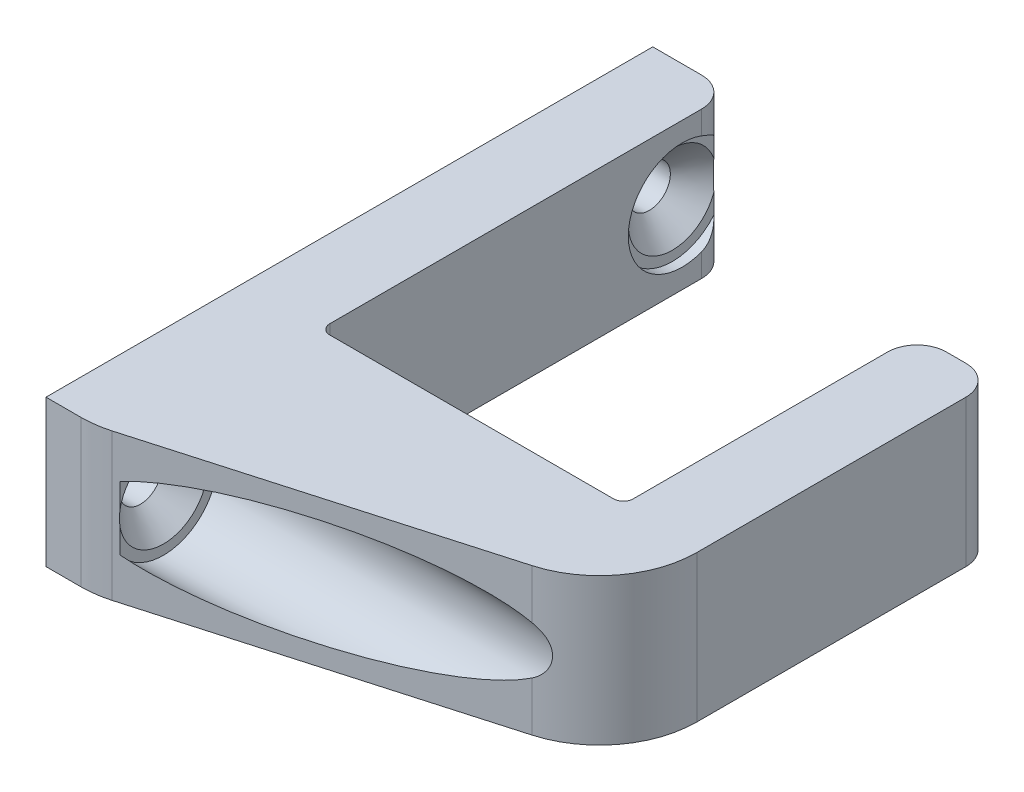
SolidWorks part; units mm, degrees
material "ABS"
ref_plane "Plan de face" through (0, 0, 0) normal (0, 0, 1) x (1, 0, 0)
ref_plane "Plan de dessus" through (0, 0, 0) normal (0, 1, 0) x (1, 0, 0)
ref_plane "Plan de droite" through (0, 0, 0) normal (1, 0, 0) x (0, 0, -1)
sketch "Esquisse1" plane through (0, 0, 0) normal (0, 1, 0) x (1, 0, 0)
  line L0 (0, 0) -> (0, 42)
  line L1 (0, 42) -> (-8, 42)
  line L2 (-8, 42) -> (-8, -20)
  line L3 (-8, -20) -> (-3, -20)
  line L4 (-3, -20) -> (39, -8)
  line L5 (39, -8) -> (39, 30)
  line L6 (39, 30) -> (31, 30)
  line L7 (31, 30) -> (31, 0)
  line L8 (31, 0) -> (0, 0)
  dimension "D1" = 20
  dimension "D2" = 8
  dimension "D3" = 30
  dimension "D4" = 12
  dimension "D5" = 8
  dimension "D6" = 8
  dimension "D7" = 5
  dimension "D8" = 31
extrude "Boss.-Extru.1" add sketch "Esquisse1" along normal mid plane 15
fillet "Congé1" radius 1 2 edges at (31, 0, 0) (0, 0, 0)
fillet "Congé2" radius 10 2 edges at (-3, 0, 20) (39, 0, 8)
fillet "Congé3" radius 3 3 edges at (31, 0, -30) (0, 0, -42) (39, 0, -30)
hole_wizard "Chambrage pour vis à tête cylindrique à 6 pans creux (ou vis CHC) M41" positions "Esquisse3" profile "Esquisse2" counterbore size "M4" standard "Ansi Metric" end condition through all
sketch "Esquisse3" plane through (0, 0, 0) normal (1, 0, 0) x (0, 0, -1)
  line L0 (-20, 7.5) -> (-20, -7.5) construction
  line L1 (42, 7.5) -> (42, -7.5) construction
  point P0 (37, 0)
  point P2 (-15, 0)
  dimension "D1" = 5
  dimension "D2" = 5
sketch "Esquisse2" plane through (0, 0, -37) normal (0, 1, 0) x (0, 0, -1)
  line L0 (0, 0) -> (0, 8)
  line L1 (0, 8) -> (2.15, 8)
  line L2 (2.15, 3.35) -> (2.15, 8)
  line L3 (2.15, 3.35) -> (4.5, 1)
  line L4 (4.5, 1) -> (5.5, 1)
  line L5 (5.5, 1) -> (5.5, 0)
  line L6 (5.5, 0) -> (5.5, -39)
  line L7 (0, 0) -> (5.5, 0) construction
  line L8 (-37.457, -39) -> (-10, -39) construction
  line L9 (-2.15, 3.35) -> (-4.5, 1) construction
  line L10 (5.5, -39) -> (0, -39)
  line L11 (0, -6.35) -> (0, 107.95) construction
  line L12 (0, -39) -> (0, 0)
  dimension "Diamètre du perçage jusqu'au prochain" = 4.3
  dimension "Profondeur du perçage jusqu'au prochain" = 8
  dimension "Diamètre du chambrage" = 11
  dimension "Profondeur du chambrage" = 1
  dimension "Diamètre du fraisage milieu" = 9
  dimension "Angle du fraisage milieu" = 90
